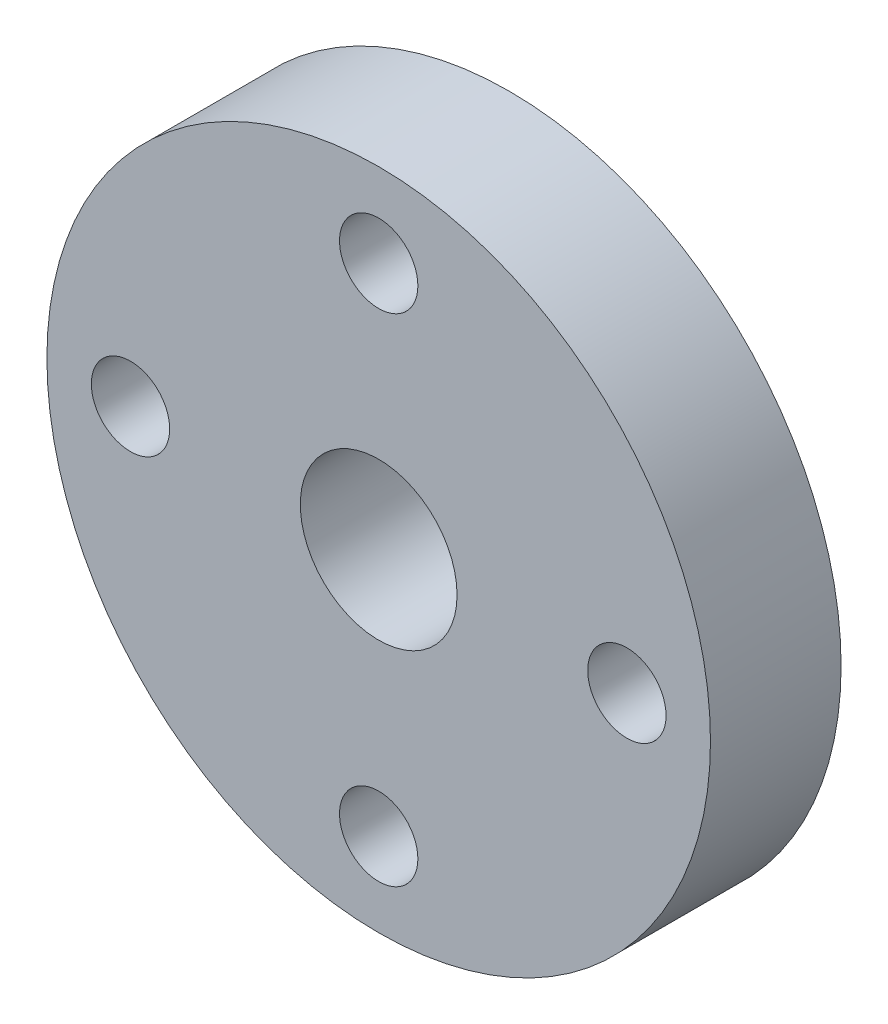
SolidWorks part; units mm, degrees
material "6061 Alloy"
ref_plane "Front Plane" through (0, 0, 0) normal (0, 0, 1) x (1, 0, 0)
ref_plane "Top Plane" through (0, 0, 0) normal (0, 1, 0) x (1, 0, 0)
ref_plane "Right Plane" through (0, 0, 0) normal (1, 0, 0) x (0, 0, -1)
sketch "Sketch1" plane through (0, 0, 0) normal (0, 0, 1) x (1, 0, 0)
  circle A0 centre (0, 0) radius 6
  circle A1 centre (0, 0) radius 3
extrude "Boss-Extrude1" add sketch "Sketch1" along normal blind 4.2
sketch "Sketch2" plane through (0, 0, 4.2) normal (0, 0, 1) x (1, 0, 0)
  circle A0 centre (0, 0) radius 3
  circle A1 centre (0, 0) radius 12.7
extrude "Boss-Extrude2" add sketch "Sketch2" along normal blind 5
sketch "Sketch3" plane through (0, 0, 9.2) normal (0, 0, 1) x (1, 0, 0)
  circle A0 centre (0, 9.4952) radius 1.5
  circle A1 centre (0, -9.5) radius 1.5
  circle A2 centre (9.5, 0) radius 1.5
  circle A3 centre (-9.5, 0) radius 1.5
  dimension "D1" = 3
  dimension "D2" = 9.5
  dimension "D3" = 9.5
  dimension "D4" = 9.4952
  dimension "D5" = 9.5
extrude "Cut-Extrude1" cut sketch "Sketch3" against normal blind 5
